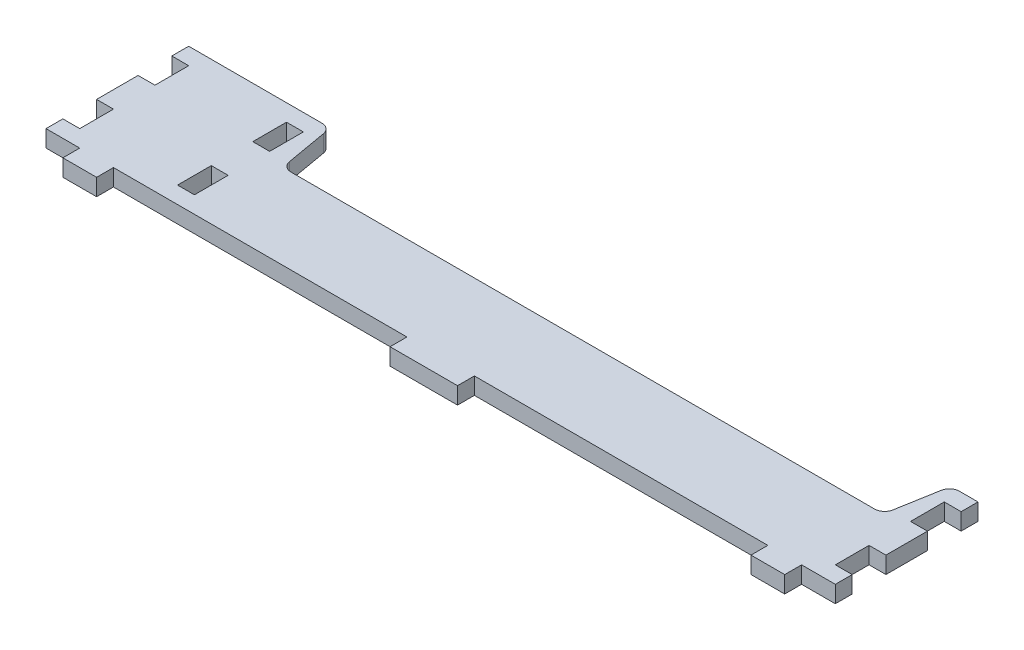
SolidWorks part; units mm, degrees
ref_plane "前视基准面" through (0, 0, 0) normal (0, 0, 1) x (1, 0, 0)
ref_plane "上视基准面" through (0, 0, 0) normal (0, 1, 0) x (1, 0, 0)
ref_plane "右视基准面" through (0, 0, 0) normal (1, 0, 0) x (0, 0, -1)
sketch "草图1" plane through (0, 0, 0) normal (0, 1, 0) x (1, 0, 0)
  line L0 (-112, 45.9997) -> (-112, -53.3706) construction
  line L1 (-117, 21.15) -> (-77.5208, 21.15)
  line L2 (-117, 21.15) -> (-117, 16.15)
  line L3 (-117, -21.15) -> (-107, -21.15)
  line L4 (117, 21.15) -> (117, 16.15)
  line L5 (-117, 21.15) -> (117, -21.15) construction
  line L6 (-117, -21.15) -> (117, 21.15) construction
  line L7 (-83, 43.8157) -> (-83, -53.3706) construction
  line L8 (112, 59.1035) -> (112, -59.3765) construction
  line L9 (-117, 6.15) -> (-117, -6.15)
  line L10 (-112, 16.15) -> (-117, 16.15)
  line L11 (-112, 16.15) -> (-112, 6.15)
  line L12 (-112, 6.15) -> (-117, 6.15)
  line L13 (-117, -16.15) -> (-117, -21.15)
  line L14 (-117, -6.15) -> (-112, -6.15)
  line L15 (-97, -21.15) -> (-10, -21.15)
  line L16 (-117, -16.15) -> (-112, -16.15)
  line L17 (-112, -6.15) -> (-112, -16.15)
  line L18 (-83, 16.15) -> (-78, 16.15)
  line L19 (-83, 16.15) -> (-83, 6.15)
  line L20 (-83, 6.15) -> (-78, 6.15)
  line L21 (-78, 16.15) -> (-78, 6.15)
  line L22 (-83, -6.15) -> (-78, -6.15)
  line L23 (-83, -6.15) -> (-83, -16.15)
  line L24 (-83, -16.15) -> (-78, -16.15)
  line L25 (-78, -6.15) -> (-78, -16.15)
  line L26 (117, 16.15) -> (112, 16.15)
  line L27 (-147.7735, 4) -> (152.0804, 4) construction
  line L28 (117, 6.15) -> (112, 6.15)
  line L29 (112, 16.15) -> (112, 6.15)
  line L30 (117, -6.15) -> (112, -6.15)
  line L31 (117, 6.15) -> (117, -6.15)
  line L32 (117, -16.15) -> (112, -16.15)
  line L33 (112, -6.15) -> (112, -16.15)
  line L34 (10, -21.15) -> (97, -21.15)
  line L35 (-107, -21.15) -> (-107, -26.15)
  line L36 (-107, -26.15) -> (-97, -26.15)
  line L37 (-97, -21.15) -> (-97, -26.15)
  line L38 (107, -21.15) -> (117, -21.15)
  line L39 (-10, -21.15) -> (-10, -26.15)
  line L40 (-10, -26.15) -> (10, -26.15)
  line L41 (10, -21.15) -> (10, -26.15)
  line L42 (117, -16.15) -> (117, -21.15)
  line L43 (97, -21.15) -> (97, -26.15)
  line L44 (97, -26.15) -> (107, -26.15)
  line L45 (107, -21.15) -> (107, -26.15)
  line L46 (-75, 30.8885) -> (-75, -41.0884) construction
  line L47 (109, 30.8885) -> (109, -38.1611) construction
  line L48 (-72, 37.0875) -> (-72, -45.7376) construction
  line L49 (106, 34.1602) -> (106, -49.0093) construction
  line L50 (-74.5656, 18.6669) -> (-72.4344, 6.4831)
  line L51 (-69.4792, 4) -> (103.4792, 4)
  line L52 (106.4344, 6.4831) -> (108.5656, 18.6669)
  line L53 (111.5208, 21.15) -> (117, 21.15)
  arc A0 (-77.5208, 21.15) -> (-74.5656, 18.6669) centre (-77.5208, 18.15) cw
  arc A1 (111.5208, 21.15) -> (108.5656, 18.6669) centre (111.5208, 18.15) ccw
  arc A2 (103.4792, 4) -> (106.4344, 6.4831) centre (103.4792, 7) ccw
  arc A3 (-69.4792, 4) -> (-72.4344, 6.4831) centre (-69.4792, 7) cw
  point P0 (0, 0)
  point P48 (-114.5, -16.15)
  point P49 (-80.5, 6.15)
  point P50 (-80.5, 16.15)
  point P51 (-10, -23.65)
  point P72 (106, 4)
  point P75 (-72, 4)
  dimension "D34" = 3
  dimension "D35" = 3
  dimension "D1" = 42.3
  dimension "D2" = 234
  dimension "D3" = 5
  dimension "D4" = 29
  dimension "D5" = 5
  dimension "D6" = 10
  dimension "D7" = 10
  dimension "D8" = 10
  dimension "D9" = 10
  dimension "D10" = 5
  dimension "D11" = 5
  dimension "D12" = 5
  dimension "D13" = 5
  dimension "D14" = 5
  dimension "D15" = 5
  dimension "D16" = 10
  dimension "D17" = 5
  dimension "D18" = 10
  dimension "D19" = 20
  dimension "D20" = 5
  dimension "D21" = 10
  dimension "D22" = 5
  dimension "D23" = 10
  dimension "D24" = 10
  dimension "D25" = 10
  dimension "D26" = 5
  dimension "D27" = 5
  dimension "D28" = 107
  dimension "D29" = 25.15
  dimension "D30" = 3
  dimension "D31" = 3
  dimension "D32" = 3
  dimension "D33" = 3
extrude "凸台-拉伸1" add sketch "草图1" along normal blind 5
